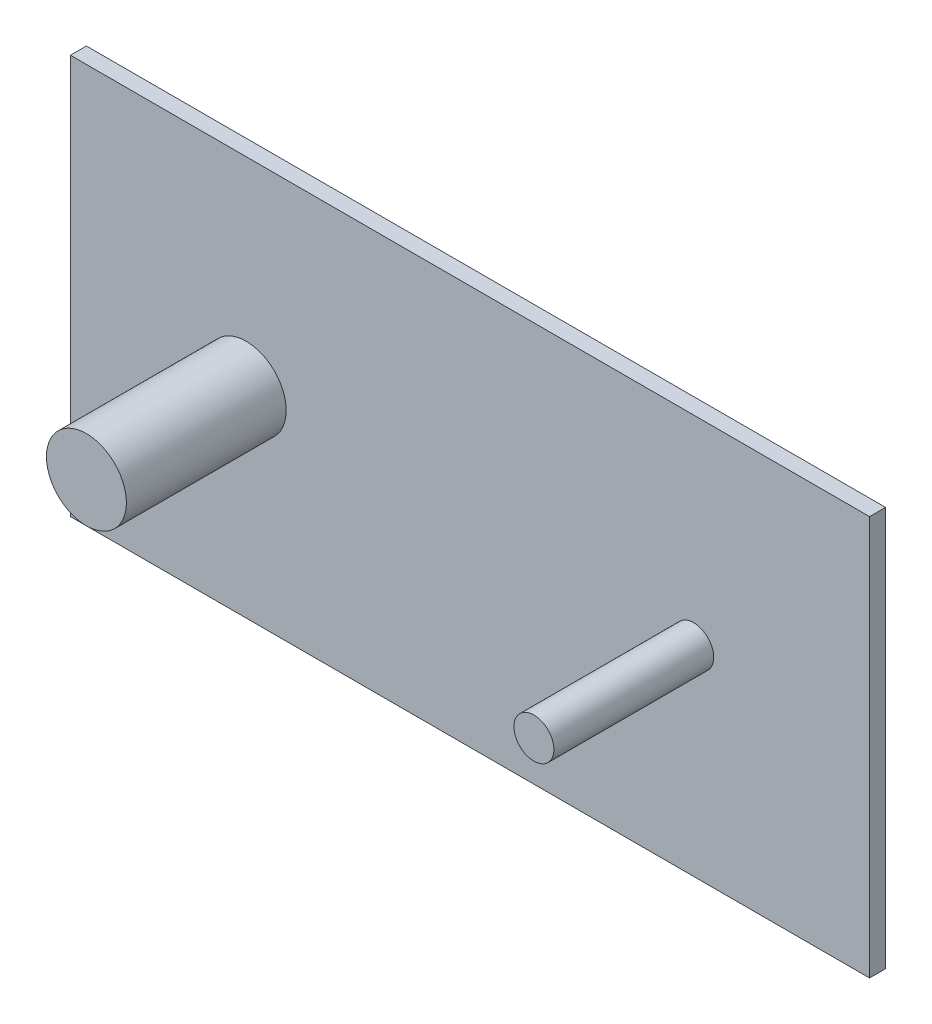
SolidWorks part; units mm, degrees
ref_plane "Front Plane" through (0, 0, 0) normal (0, 0, 1) x (1, 0, 0)
ref_plane "Top Plane" through (0, 0, 0) normal (0, 1, 0) x (1, 0, 0)
ref_plane "Right Plane" through (0, 0, 0) normal (1, 0, 0) x (0, 0, -1)
sketch "Sketch1" plane through (0, 0, 0) normal (0, 0, 1) x (1, 0, 0)
  line L0 (-140, 0) -> (140, 0) construction
  line L1 (-250, -125) -> (250, -125)
  line L2 (-250, -125) -> (-250, 125)
  line L3 (-250, 125) -> (250, 125)
  line L4 (250, -125) -> (250, 125)
  line L5 (-250, -125) -> (250, 125) construction
  line L6 (-250, 125) -> (250, -125) construction
  point P0 (0, 0)
  point P9 (0, 0)
  dimension "D1" = 500
  dimension "D2" = 250
  dimension "D3" = 280
extrude "Boss-Extrude1" add sketch "Sketch1" along normal blind 10
sketch "Sketch2" plane through (0, 0, 10) normal (0, 0, 1) x (1, 0, 0)
  line L0 (-140, 0) -> (140, 0) construction
  line L1 (-140, 0) -> (140, 0) construction
  circle A0 centre (-140, 0) radius 25
  circle A1 centre (140, 0) radius 12.5
  dimension "D1" = 25
  dimension "D2" = 50
extrude "Boss-Extrude2" add sketch "Sketch2" along normal blind 100
